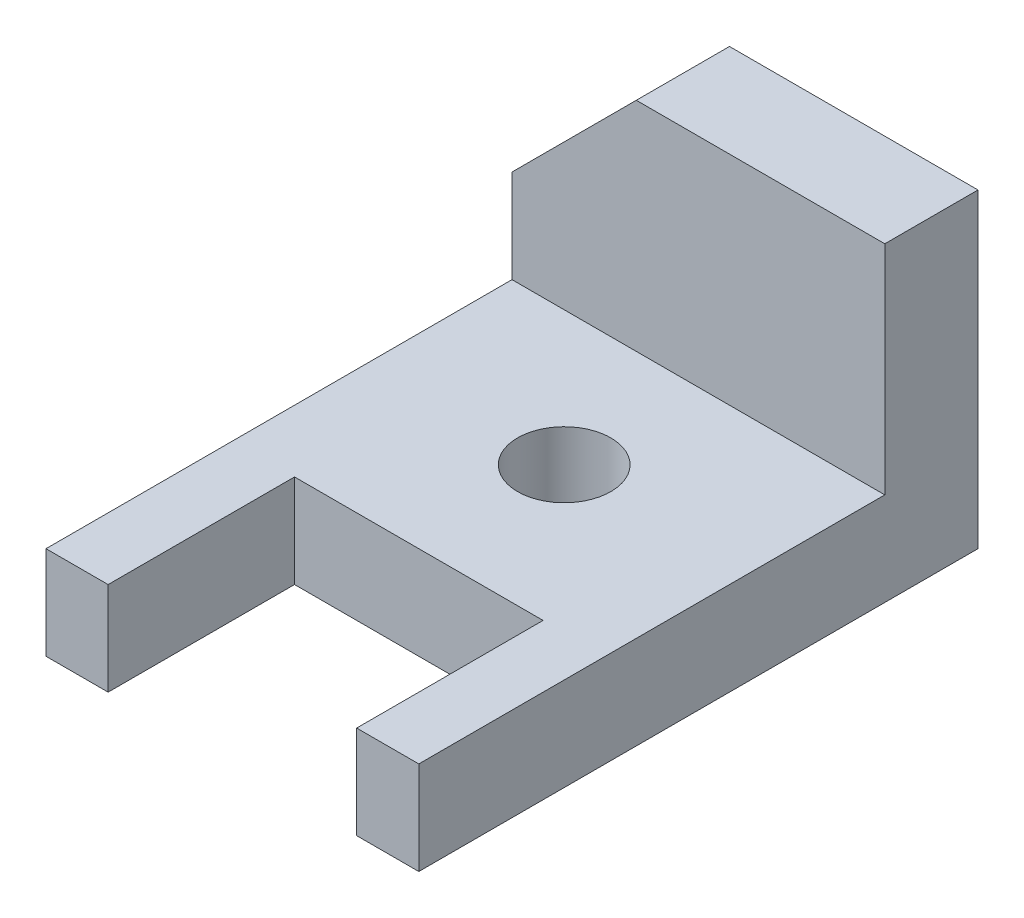
SolidWorks part; units mm, degrees
ref_plane "Front Plane" through (0, 0, 0) normal (0, 0, 1) x (1, 0, 0)
ref_plane "Top Plane" through (0, 0, 0) normal (0, 1, 0) x (1, 0, 0)
ref_plane "Right Plane" through (0, 0, 0) normal (1, 0, 0) x (0, 0, -1)
sketch "Sketch1" plane through (0, 0, 0) normal (0, 1, 0) x (1, 0, 0)
  line L1 (-97.2845, -21.0845) -> (-173.4845, -21.0845)
  line L2 (-97.2845, -21.0845) -> (-97.2845, 93.2155)
  line L3 (-97.2845, 93.2155) -> (-173.4845, 93.2155)
  line L4 (-173.4845, -21.0845) -> (-173.4845, 93.2155)
  dimension "D1" = 114.3
  dimension "D2" = 76.2
extrude "Boss-Extrude1" add sketch "Sketch1" along normal blind 19.05
sketch "Sketch3" plane through (0, 0, 0) normal (0, -1, 0) x (1, 0, 0)
  line L0 (-173.4845, -93.2155) -> (-173.4845, 21.0845) construction
  line L1 (-97.2845, -93.2155) -> (-173.4845, -93.2155)
  line L2 (-97.2845, -93.2155) -> (-97.2845, -74.1655)
  line L3 (-97.2845, -74.1655) -> (-173.4845, -74.1655)
  line L4 (-173.4845, -93.2155) -> (-173.4845, -74.1655)
  dimension "D1" = 19.05
extrude "Boss-Extrude2" add sketch "Sketch3" against normal blind 63.5
hole_wizard "3/4 (0.75) Diameter Hole1" positions "Sketch8" profile "Sketch9" hole size "3/4" standard "ANSI Inch" end condition through all
sketch "Sketch8" plane through (0, 19.05, 0) normal (0, 1, 0) x (1, 0, 0)
  line L1 (-173.4845, -21.0845) -> (-97.2845, -21.0845) construction
  line L2 (-173.4845, 74.1655) -> (-173.4845, -21.0845) construction
  point P0 (-135.3845, 46.7335)
  dimension "D1" = 67.818
  dimension "D2" = 38.1
sketch "Sketch9" plane through (-135.3845, 19.05, -46.7335) normal (1, 0, 0) x (0, 0, 1)
  line L0 (0, 0) -> (0, 19.05)
  line L1 (0, 19.05) -> (9.525, 19.05)
  line L2 (9.525, 19.05) -> (9.525, 0)
  line L5 (9.525, 0) -> (0, 0)
  line L11 (0, -6.35) -> (0, 107.95) construction
  dimension "Thru Hole Dia." = 19.05
  dimension "Thru Hole Depth" = 19.05
sketch "Sketch10" plane through (0, 0, 21.0845) normal (0, 0, 1) x (1, 0, 0)
  line L0 (-173.4845, 19.05) -> (-97.2845, 19.05) construction
  line L1 (-160.7845, 19.05) -> (-109.9845, 19.05)
  line L2 (-160.7845, 19.05) -> (-160.7845, 0)
  line L3 (-160.7845, 0) -> (-109.9845, 0)
  line L4 (-109.9845, 19.05) -> (-109.9845, 0)
  line L5 (-173.4845, 0) -> (-97.2845, 0) construction
  line L6 (-173.4845, 19.05) -> (-173.4845, 0) construction
  dimension "D1" = 50.8
  dimension "D2" = 12.7
extrude "Boss-Extrude3" add sketch "Sketch10" against normal blind 38.1
sketch "Sketch12" plane through (0, 0, 21.0845) normal (0, 0, 1) x (1, 0, 0)
  line L0 (-173.4845, 19.05) -> (-97.2845, 19.05) construction
  line L1 (-160.7845, 19.05) -> (-109.9845, 19.05)
  line L2 (-160.7845, 19.05) -> (-160.7845, 0)
  line L3 (-160.7845, 0) -> (-109.9845, 0)
  line L4 (-109.9845, 19.05) -> (-109.9845, 0)
  line L5 (-173.4845, 0) -> (-97.2845, 0) construction
  line L6 (-173.4845, 19.05) -> (-173.4845, 0) construction
  dimension "D1" = 12.7
  dimension "D2" = 50.8
extrude "Cut-Extrude1" cut sketch "Sketch12" against normal blind 38.1
sketch "Sketch13" plane through (0, 0, -74.1655) normal (0, 0, 1) x (1, 0, 0)
  line L0 (-173.4845, 38.1) -> (-148.0845, 63.5)
  line L1 (-173.4845, 63.5) -> (-173.4845, 19.05) construction
  line L2 (-97.2845, 63.5) -> (-173.4845, 63.5) construction
  line L3 (-148.0845, 63.5) -> (-173.4845, 63.5)
  line L4 (-173.4845, 63.5) -> (-173.4845, 38.1)
  line L5 (-97.2845, 63.5) -> (-97.2845, 19.05) construction
  dimension "D1" = 50.8
  dimension "D2" = 25.4
extrude "Cut-Extrude2" cut sketch "Sketch13" against normal blind 38.1
